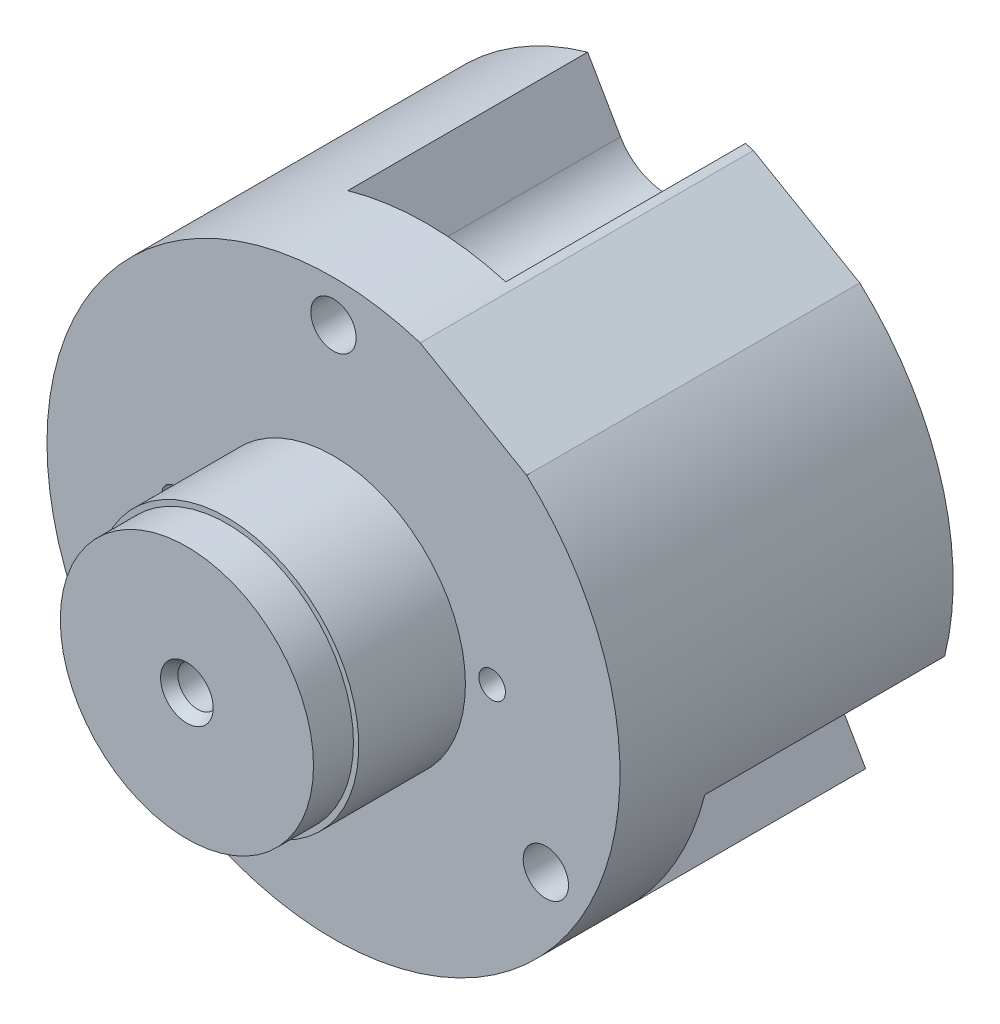
SolidWorks part; units mm, degrees
ref_plane "Front Plane" through (0, 0, 0) normal (0, 0, 1) x (1, 0, 0)
ref_plane "Top Plane" through (0, 0, 0) normal (0, 1, 0) x (1, 0, 0)
ref_plane "Right Plane" through (0, 0, 0) normal (1, 0, 0) x (0, 0, -1)
ref_plane "Ebene1" through (0, 0, 23) normal (0, 0, 1) x (1, 0, 0)
sketch "Skizze1" plane through (0, 0, 23) normal (0, 0, 1) x (1, 0, 0)
  line L0 (14.4922, 15.8816) -> (6.5078, 20.4914)
  arc A0 (6.5078, 20.4914) -> (14.4922, 15.8816) centre (0, 0) ccw
extrude "Aufsatz-Linear austragen1" add sketch "Skizze1" against normal blind 25
sketch "Skizze2" plane through (0, 0, -2) normal (0, 0, -1) x (-1, 0, 0)
  line L0 (3.4641, 16.4) -> (5.9275, 20.6668)
  line L1 (-5.9275, 20.6668) -> (-3.4641, 16.4)
  arc A0 (5.9275, 20.6668) -> (-5.9275, 20.6668) centre (0, 0) ccw
  arc A1 (-3.4641, 16.4) -> (3.4641, 16.4) centre (0, 18.4) ccw
extrude "Schnitt-Linear austragen1" cut sketch "Skizze2" against normal blind 18
sketch "Skizze3" plane through (0, 0, -2) normal (0, 0, -1) x (-1, 0, 0)
  line L0 (12.4708, -11.2) -> (14.9342, -15.4668)
  line L1 (20.8617, -5.2) -> (15.9349, -5.2)
  arc A0 (14.9342, -15.4668) -> (20.8617, -5.2) centre (0, 0) ccw
  arc A1 (15.9349, -5.2) -> (12.4708, -11.2) centre (15.9349, -9.2) ccw
extrude "Schnitt-Linear austragen2" cut sketch "Skizze3" against normal blind 18
sketch "Skizze4" plane through (0, 0, -2) normal (0, 0, -1) x (-1, 0, 0)
  line L0 (-15.9349, -5.2) -> (-20.8617, -5.2)
  line L1 (-14.9342, -15.4668) -> (-12.4708, -11.2)
  arc A0 (-20.8617, -5.2) -> (-14.9342, -15.4668) centre (0, 0) ccw
  arc A1 (-12.4708, -11.2) -> (-15.9349, -5.2) centre (-15.9349, -9.2) ccw
extrude "Schnitt-Linear austragen3" cut sketch "Skizze4" against normal blind 18
ref_plane "Ebene4" through (0, 0, 0) normal (0, -1, 0) x (1, 0, 0)
sketch "Skizze7" plane through (0, 0, 0) normal (0, -1, 0) x (1, 0, 0)
  line L0 (9.5, 34) -> (0, 34)
  line L1 (0, 34) -> (0, 23)
  line L2 (0, 23) -> (9.9, 23)
  line L3 (9.9, 23) -> (9.9, 31)
  line L4 (9.9, 31) -> (9.5, 31)
  line L5 (9.5, 31) -> (9.5, 34)
  line L6 (0, 34) -> (0, 23) construction
revolve "Rotation1" add sketch "Skizze7" angle 360 about L6
hole_wizard "Ø3.4 (3.4) Durchmesser Bohrung1" positions "Skizze11" profile "Skizze10" hole size "Ø3.4" standard "ANSI Metrisch"
sketch "Skizze11" plane through (0, 0, 16) normal (0, 0, -1) x (-1, 0, 0)
  point P0 (0, 18.4)
  point P1 (15.9349, -9.2)
  point P2 (-15.9349, -9.2)
sketch "Skizze10" plane through (0, 18.4, 16) normal (1, 0, 0) x (0, 1, 0)
  line L0 (0, 0) -> (0, 18)
  line L1 (0, 18) -> (1.7, 18)
  line L2 (1.7, 18) -> (1.7, 0)
  line L5 (1.7, 0) -> (0, 0)
  line L11 (0, -6.35) -> (0, 107.95) construction
  dimension "Bohrerdurchmesser" = 3.4
  dimension "Bohrungstiefe" = 18
hole_wizard "Ø3.0 (3) Durchmesser Bohrung2" positions "Skizze21" profile "Skizze20" hole size "Ø3.0" standard "DIN" end condition through all
sketch "Skizze21" plane through (0, 0, 34) normal (0, 0, 1) x (1, 0, 0)
  point P0 (0, 0)
sketch "Skizze20" plane through (0, 0, 34) normal (1, 0, 0) x (0, -1, 0)
  line L0 (0, 0) -> (0, 36)
  line L1 (0, 36) -> (1.5, 36)
  line L2 (1.5, 36) -> (1.5, 0)
  line L5 (1.5, 0) -> (0, 0)
  line L11 (0, -6.35) -> (0, 107.95) construction
  dimension "Bohrerdurchmesser" = 3
  dimension "Bohrungstiefe" = 36
chamfer "Fase1" distance 0.475 angle 60 1 edges at (1.5, 0, 34)
hole_wizard "M3 Gewindebohrung1" positions "Skizze22" profile "Skizze23" tap size "M3" standard "DIN"
sketch "Skizze22" plane through (0, 0, -2) normal (0, 0, -1) x (-1, 0, 0)
  line L0 (-10.5, 18.1865) -> (0, 0) construction
  line L1 (-14.4922, 15.8816) -> (-6.5078, 20.4914) construction
  line L3 (-12.4708, -7.2) -> (0, 0) construction
  arc A1 (-12.4708, -11.2) -> (-15.9349, -5.2) centre (-15.9349, -9.2) ccw construction
  point P0 (-8.5, 14.7224)
  point P23 (8.5, -14.7224)
  dimension "D1" = 34
cosmetic thread "Bohrungsgewinde1" parameters "D1"=6, "D2"=3
cosmetic thread "Bohrungsgewinde2" parameters "D1"=6, "D2"=3
sketch "Skizze23" plane through (8.5, 14.7224, -2) normal (1, 0, 0) x (0, 1, 0)
  line L0 (0, 0) -> (0, 9.2511)
  line L1 (0, 9.2511) -> (1.25, 8.5)
  line L2 (1.25, 8.5) -> (1.25, 0)
  line L5 (1.25, 0) -> (0, 0)
  line L10 (0, 9.2511) -> (-1.25, 8.5) construction
  line L11 (0, -6.35) -> (0, 107.95) construction
  dimension "Bohrerdurchmesser" = 2.5
  dimension "Bohrungstiefe" = 8.5
  dimension "Spitzenwinkel" = 118
hole_wizard "Ø2.5 (2.5) Durchmesser Bohrung4" positions "Skizze24" profile "Skizze26" hole size "Ø2.5" standard "DIN"
sketch "Skizze24" plane through (0, 0, -2) normal (0, 0, -1) x (-1, 0, 0)
  line L0 (-10.5, 18.1865) -> (0, 0) construction
  line L1 (-14.4922, 15.8816) -> (-6.5078, 20.4914) construction
  line L2 (0, 0) -> (-12.4708, -7.2) construction
  arc A0 (-12.4708, -11.2) -> (-15.9349, -5.2) centre (-15.9349, -9.2) ccw construction
  point P0 (-5.5491, 9.4979)
  point P15 (5.4509, -9.5546)
  dimension "D1" = 22
sketch "Skizze26" plane through (5.5491, 9.4979, -2) normal (1, 0, 0) x (0, 1, 0)
  line L0 (0, 0) -> (0, 6.7511)
  line L1 (0, 6.7511) -> (1.25, 6)
  line L2 (1.25, 6) -> (1.25, 0)
  line L5 (1.25, 0) -> (0, 0)
  line L10 (0, 6.7511) -> (-1.25, 6) construction
  line L11 (0, -6.35) -> (0, 107.95) construction
  dimension "Bohrerdurchmesser" = 2.5
  dimension "Bohrungstiefe" = 6
  dimension "Spitzenwinkel" = 118
hole_wizard "Ø2.0mm Stiftloch1" positions "Skizze27" profile "Skizze28" hole size "Ø2.0" standard "DIN"
sketch "Skizze27" plane through (0, 0, 23) normal (0, 0, 1) x (1, 0, 0)
  line L6 (-15.9349, -9.2) -> (0, 0) construction
  line L7 (0, 0) -> (18.6195, 10.75) construction
  line L8 (0, 0) -> (10.75, -18.6195) construction
  arc A1 (6.5078, 20.4914) -> (14.4922, 15.8816) centre (0, 0) ccw construction
  point P0 (-11.887, 0.989)
  point P2 (11.9031, 0.9833)
  dimension "D1" = 5.1
  dimension "D2" = 6.8
  dimension "D3" = 10.8
  dimension "D4" = 9.8
sketch "Skizze28" plane through (-11.887, 0.989, 23) normal (1, 0, 0) x (0, -1, 0)
  line L0 (0, 0) -> (0, 9.1009)
  line L1 (0, 9.1009) -> (1, 8.5)
  line L2 (1, 8.5) -> (1, 0)
  line L5 (1, 0) -> (0, 0)
  line L10 (0, 9.1009) -> (-1, 8.5) construction
  line L11 (0, -6.35) -> (0, 107.95) construction
  dimension "Bohrerdurchmesser" = 2
  dimension "Bohrungstiefe" = 8.5
  dimension "Spitzenwinkel" = 118
